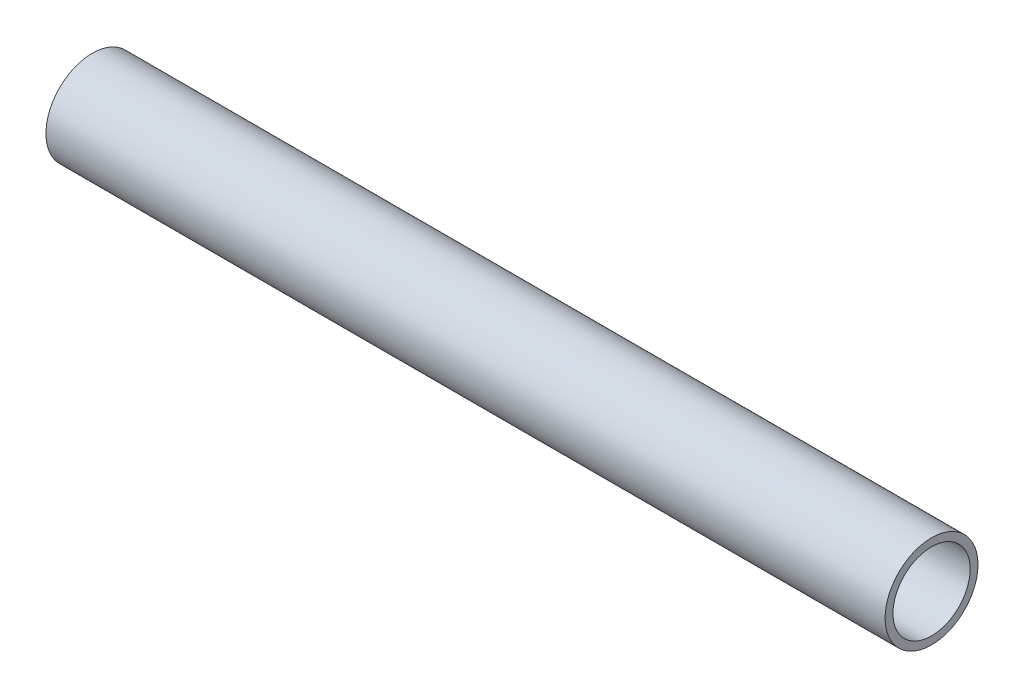
SolidWorks part; units mm, degrees
material "Plain Carbon Steel"
ref_plane "Front Plane" through (0, 0, 0) normal (0, 0, 1) x (1, 0, 0)
ref_plane "Top Plane" through (0, 0, 0) normal (0, 1, 0) x (1, 0, 0)
ref_plane "Right Plane" through (0, 0, 0) normal (1, 0, 0) x (0, 0, -1)
sketch "Sketch1" plane through (0, 0, 0) normal (1, 0, 0) x (0, 0, -1)
  circle A0 centre (0, 0) radius 21.082
  circle A1 centre (0, 0) radius 17.526
  dimension "D1" = 42.164
  dimension "D2" = 35.052
extrude "Boss-Extrude1" add sketch "Sketch1" along normal mid plane 381
